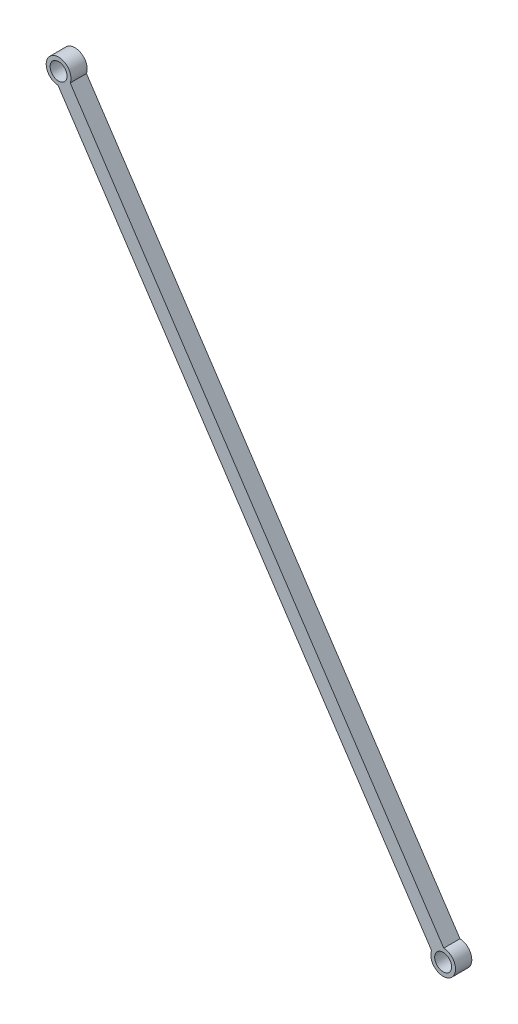
SolidWorks part; units mm, degrees
ref_plane "Front Plane" through (0, 0, 0) normal (0, 0, 1) x (1, 0, 0)
ref_plane "Top Plane" through (0, 0, 0) normal (0, 1, 0) x (1, 0, 0)
ref_plane "Right Plane" through (0, 0, 0) normal (1, 0, 0) x (0, 0, -1)
sketch "Sketch1" plane through (0, 0, 0) normal (0, 0, 1) x (1, 0, 0)
  line L0 (-6.1517, -3.239) -> (-35.6905, 41.2451) construction
  line L1 (-7.0436, -2.9121) -> (-35.7352, 40.2962)
  line L2 (-6.1069, -2.2901) -> (-34.7985, 40.9182)
  arc A0 (-34.7985, 40.9182) -> (-35.7352, 40.2962) centre (-35.6905, 41.2451) ccw
  circle A1 centre (-6.1517, -3.239) radius 0.65
  arc A3 (-7.0436, -2.9121) -> (-6.1069, -2.2901) centre (-6.1517, -3.239) ccw
  circle A5 centre (-35.6905, 41.2451) radius 0.65
  circle A9 centre (-35.6905, 41.2451) radius 0.65 construction
  circle A10 centre (-6.1517, -3.239) radius 0.65 construction
extrude "Boss-Extrude1" add sketch "Sketch1" along normal up to surface (1.25 mm away)
